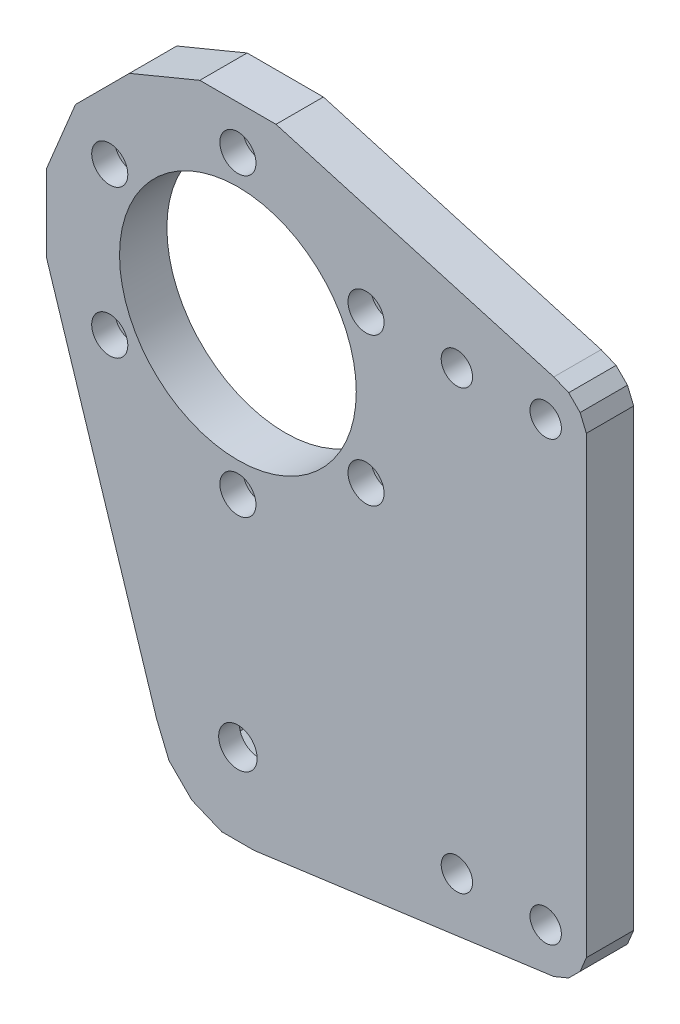
SolidWorks part; units mm, degrees
ref_plane "前视基准面" through (0, 0, 0) normal (0, 0, 1) x (1, 0, 0)
ref_plane "上视基准面" through (0, 0, 0) normal (0, 1, 0) x (1, 0, 0)
ref_plane "右视基准面" through (0, 0, 0) normal (1, 0, 0) x (0, 0, -1)
other "Configuration Table"
sketch "Profile_1" plane through (0, 0, 0) normal (0, 0, 1) x (1, 0, 0)
  line L0 (57.8203, 15.889) -> (55.889, 17.8203)
  line L1 (55.889, 17.8203) -> (53.3656, 18.8655)
  line L2 (53.3656, 18.8655) -> (6.438, 32.3659)
  line L3 (6.438, 32.3659) -> (-6.438, 32.3659)
  line L4 (-6.438, 32.3659) -> (-18.3338, 27.4385)
  line L5 (-18.3338, 27.4385) -> (-27.4385, 18.3338)
  line L6 (-27.4385, 18.3338) -> (-32.3659, 6.438)
  line L7 (-32.3659, 6.438) -> (-32.3659, -6.438)
  line L8 (-32.3659, -6.438) -> (-13.731, -64.7313)
  line L9 (-13.731, -64.7313) -> (-11.6406, -69.778)
  line L10 (-11.6406, -69.778) -> (-7.778, -73.6406)
  line L11 (-7.778, -73.6406) -> (-2.7313, -75.731)
  line L12 (-2.7313, -75.731) -> (2.7313, -75.731)
  line L13 (2.7313, -75.731) -> (53.3656, -68.8655)
  line L14 (53.3656, -68.8655) -> (55.889, -67.8203)
  line L15 (55.889, -67.8203) -> (57.8203, -65.889)
  line L16 (57.8203, -65.889) -> (58.8655, -63.3656)
  line L17 (58.8655, -63.3656) -> (58.8655, 13.3656)
  line L18 (58.8655, 13.3656) -> (57.8203, 15.889)
  circle A0 centre (0, 0) radius 20
  circle A1 centre (0, -62) radius 3.25
  circle A2 centre (-21.6506, 12.5) radius 1.65
  circle A3 centre (0, 25) radius 1.65
  circle A4 centre (21.6506, 12.5) radius 1.65
  circle A5 centre (21.6506, -12.5) radius 1.65
  circle A6 centre (0, -25) radius 1.65
  circle A7 centre (-21.6506, -12.5) radius 1.65
  circle A8 centre (52, 12) radius 2.65
  circle A9 centre (37, 12) radius 2.65
  circle A10 centre (52, -62) radius 2.65
  circle A11 centre (37, -62) radius 2.65
extrude "Frame_and_bench_interface" add sketch "Profile_1" along normal blind 8 from offset 1
sketch "Profile_2" plane through (0, 0, 0) normal (0, 0, 1) x (1, 0, 0)
  circle A0 centre (-21.6506, 12.5) radius 3.05
  circle A1 centre (0, 25) radius 3.05
  circle A2 centre (21.6506, 12.5) radius 3.05
  circle A3 centre (21.6506, -12.5) radius 3.05
  circle A4 centre (0, -25) radius 3.05
  circle A5 centre (-21.6506, -12.5) radius 3.05
extrude "Recess_stator_screw_heads" cut sketch "Profile_2" along normal blind 4 from offset 3.1
sketch "Profile_3" plane through (0, 0, 0) normal (0, 0, 1) x (1, 0, 0)
  line L0 (-5.175, -64.9878) -> (0, -67.9756)
  line L1 (0, -67.9756) -> (5.175, -64.9878)
  line L2 (5.175, -64.9878) -> (5.175, -59.0122)
  line L3 (5.175, -59.0122) -> (0, -56.0244)
  line L4 (0, -56.0244) -> (-5.175, -59.0122)
  line L5 (-5.175, -59.0122) -> (-5.175, -64.9878)
extrude "Rear_captive_nut_B" cut sketch "Profile_3" along normal blind 4.51 from offset 1.01
